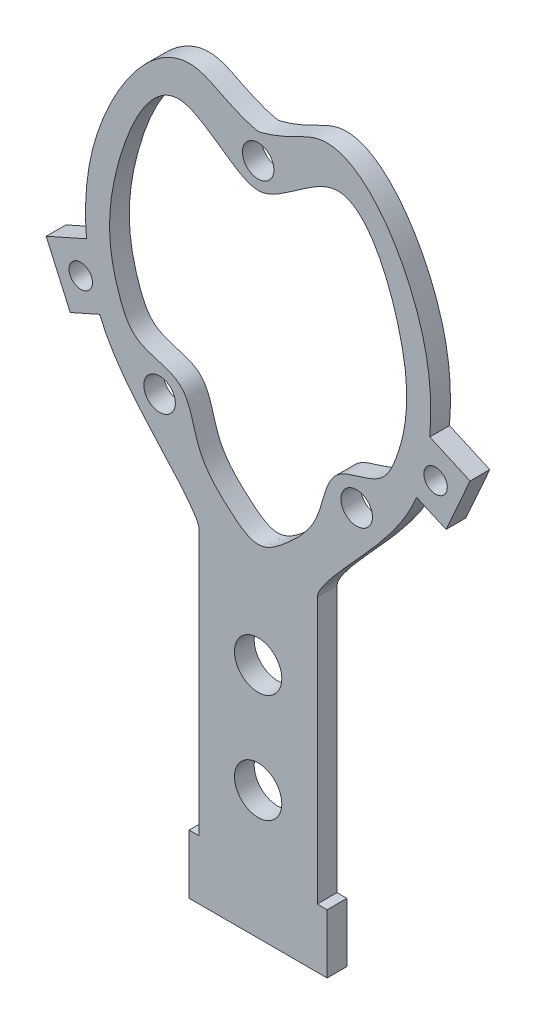
SolidWorks part; units mm, degrees
ref_plane "Front Plane" through (0, 0, 0) normal (0, 0, 1) x (1, 0, 0)
ref_plane "Top Plane" through (0, 0, 0) normal (0, 1, 0) x (1, 0, 0)
ref_plane "Right Plane" through (0, 0, 0) normal (1, 0, 0) x (0, 0, -1)
sketch "Sketch2" plane through (0, 0, 0) normal (0, 0, 1) x (1, 0, 0)
  line L0 (0, -0.0188) -> (0, -6.781) construction
  line L1 (-1.25, 4.75) -> (1.25, 4.75) construction
  line L2 (-4, 6.25) -> (4, 6.25) construction
  line L3 (-7.2, 1.5) -> (7.2, 1.5) construction
  line L4 (-6.25, -5.25) -> (6.25, -5.25) construction
  line L5 (-4, -6.25) -> (4, -6.25) construction
  line L6 (-3, -8.55) -> (3, -8.55) construction
  line L7 (-1.4, -10.55) -> (1.4, -10.55) construction
  line L8 (-5, -7.2) -> (-6.1491, -8.1642) construction
  line L9 (-7, -4) -> (7, -4) construction
  line L10 (0, 1.0146) -> (0, -5.7476) construction
  line L11 (-1, 7.15) -> (1, 7.15) construction
  line L12 (-3.1, 8.05) -> (3.1, 8.05) construction
  line L13 (-8.4144, 1.7962) -> (8.4144, 1.7962) construction
  line L14 (-6.1491, -8.1642) -> (6.1491, -8.1642) construction
  line L16 (-0.5007, -40.6671) -> (-6.3266, 25.9227) construction
  line L17 (-3, -12.1) -> (3, -12.1) construction
  line L18 (-8.6856, -2.4538) -> (8.6856, -2.4538) construction
  line L19 (6.2221, 24.7292) -> (0.3963, -41.8606) construction
  line L20 (-28.4032, 6.85) -> (28.4032, 6.85) construction
  line L21 (-7.2, 1.5) -> (-8.4144, 1.7962) construction
  line L22 (-8.6856, -2.4538) -> (-7.4495, -2.2683) construction
  line L23 (-3, -25.6) -> (-3.5, -25.6)
  line L24 (-3, -12.1) -> (3, -12.1) construction
  line L25 (-3, -12.1) -> (-3, -25.6)
  line L26 (-3, -25.6) -> (3, -25.6) construction
  line L27 (3, -12.1) -> (3, -25.6)
  line L28 (-3, -12.1) -> (3, -25.6) construction
  line L29 (-3, -25.6) -> (3, -12.1) construction
  line L30 (-3.5, -25.6) -> (3.5, -25.6) construction
  line L31 (-3.5, -25.6) -> (-3.5, -28.6)
  line L32 (-3.5, -28.6) -> (3.5, -28.6)
  line L33 (3.5, -25.6) -> (3.5, -28.6)
  line L34 (-3.5, -25.6) -> (3.5, -28.6) construction
  line L35 (-3.5, -28.6) -> (3.5, -25.6) construction
  line L36 (3.5, -25.6) -> (3, -25.6)
  circle A2 centre (0, -16.6) radius 1.2
  circle A3 centre (0, 5.55) radius 0.8
  circle A4 centre (-5, -7.2) radius 0.8
  circle A5 centre (5, -7.2) radius 0.8
  circle A6 centre (0, -22.1) radius 1.2
  spline S0 degree 3 poles (1.8069, 5.0163) (0, 4.0197) (-1.8069, 5.0163) (-4.9012, 7.7541) (-7.771, 1.1281) (-7.6313, -2.6614) (-6.2568, -5.758) (-3.5015, -5.7609) (-3.2301, -8.7844) (-1.7453, -10.314) (0, -11.6774) (1.7453, -10.314) (3.2301, -8.7844) (3.5015, -5.7609) (6.2568, -5.758) (7.6313, -2.6614) (7.771, 1.1281) (4.9012, 7.7541) (1.8069, 5.0163) (0, 4.0197) (-1.8069, 5.0163) knots -0.194127 -0.085189 -0.025607 0 0.025607 0.085189 0.194127 0.29881 0.326537 0.37337 0.421074 0.469791 0.5 0.530209 0.578926 0.62663 0.673463 0.70119 0.805873 0.914811 0.974393 1 1.025607 1.085189 1.194127 only from (0, 4.25) to (0, 4.25)
  spline S1 degree 3 poles (3, -12.1) (3.0581, -11.4359) (7.3722, -7.2617) (8.8163, -3.8196) (8.7952, 3.0882) (4.7299, 9.5027) (1.5431, 7.2852) (0.1384, 6.8487) (-0.1384, 6.8487) (-1.5431, 7.2852) (-4.7299, 9.5027) (-8.7952, 3.0882) (-8.8163, -3.8196) (-7.3722, -7.2617) (-3.0581, -11.4359) (-3, -12.1) knots 0.110532 0.110532 0.110532 0.110532 0.195871 0.310872 0.37508 0.502014 0.537662 0.553506 0.557026 0.57287 0.608518 0.735452 0.79966 0.914661 1 1 1 1
  point P5 (0, 0)
  point P9 (0, -6.25)
  point P40 (0, -2.2618)
  point P45 (0, -27.1)
  point P51 (0, 4.75)
  point P58 (0, 6.25)
  point P60 (0, 1.5)
  point P62 (0, -4)
  point P64 (0, -5.25)
  point P68 (0, -8.55)
  point P86 (0, -12.1)
  point P89 (0, 7.15)
  point P90 (0, 8.05)
  point P91 (0, 1.7962)
  point P92 (0, -2.4538)
  point P93 (0, -8.1642)
  point P100 (0, -10.55)
  point P101 (0, -25.6)
  point P102 (0, -18.85)
  dimension "D32" = 1
  dimension "D36" = 2
  dimension "D37" = 2
  dimension "D40" = 1.6
  dimension "D6" = 0.5
  dimension "D46" = 2.4
  dimension "D1" = 6
  dimension "D2" = 13.5
  dimension "D3" = 1.5
  dimension "D5" = 7.2
  dimension "D7" = 2.6
  dimension "D8" = 4.25
  dimension "D9" = 1.25
  dimension "D10" = 2
  dimension "D11" = 4
  dimension "D12" = 0.3
  dimension "D13" = 0.9
  dimension "D14" = 3.1
  dimension "D15" = 4
  dimension "D16" = 7
  dimension "D17" = 1.25
  dimension "D18" = 5.25
  dimension "D19" = 6.25
  dimension "D20" = 6.25
  dimension "D21" = 4
  dimension "D22" = 8.55
  dimension "D23" = 3
  dimension "D24" = 1.5
  dimension "D25" = 40
  dimension "D26" = 10
  dimension "D27" = 10.55
  dimension "D28" = 1.4
  dimension "D29" = 11.3
  dimension "D31" = 0.8
  dimension "D33" = 90
  dimension "D34" = 1
  dimension "D35" = 1.25
  dimension "D38" = 175
  dimension "D39" = 175
  dimension "D41" = 1.3
  dimension "D42" = 12.75
  dimension "D43" = 5
  dimension "D44" = 3
  dimension "D45" = 7
  dimension "D47" = 3.5
  dimension "D48" = 5.5
extrude "Boss-Extrude2" add sketch "Sketch2" along normal blind 1 separate body
sketch "Sketch3" plane through (0, 0, 0) normal (0, 0, 1) x (1, 0, 0)
  line L0 (-7.4013, -3.2882) -> (-10.1419, -4.5084) construction
  line L5 (-8.0114, -1.9179) -> (-6.7912, -4.6585)
  line L6 (-8.0114, -1.9179) -> (-10.752, -3.1381)
  line L8 (-10.752, -3.1381) -> (-9.5318, -5.8787)
  line L9 (-6.7912, -4.6585) -> (-9.5318, -5.8787)
  line L10 (0, 0) -> (0, -5.2835) construction
  line L11 (-8.0114, -1.9179) -> (-10.752, -3.1381)
  line L12 (-6.7912, -4.6585) -> (-9.5318, -5.8787)
  line L13 (7.4013, -3.2882) -> (10.1419, -4.5084) construction
  line L14 (6.7912, -4.6585) -> (9.5318, -5.8787)
  line L15 (8.0114, -1.9179) -> (10.752, -3.1381)
  line L16 (6.7912, -4.6585) -> (9.5318, -5.8787)
  line L17 (10.752, -3.1381) -> (9.5318, -5.8787)
  line L18 (8.0114, -1.9179) -> (10.752, -3.1381)
  line L19 (8.0114, -1.9179) -> (6.7912, -4.6585)
  point P5 (-9, -4)
  point P25 (9, -4)
  dimension "D1" = 3
  dimension "D2" = 24
  dimension "D3" = 1.25
  dimension "D4" = 9
  dimension "D5" = 4
extrude "Boss-Extrude3" add sketch "Sketch3" along normal blind 1 contours L9 L5 L6 L8 | L15 L19 L14 L17
sketch "Sketch4" plane through (0, 0, 0) normal (0, 0, 1) x (1, 0, 0)
  line L0 (-10.1419, -4.5084) -> (-9, -4) construction
  line L3 (-10.752, -3.1381) -> (-9.5318, -5.8787) construction
  line L6 (-8.7065, -2.2274) -> (-10.752, -3.1381) construction
  line L7 (0, 0) -> (0, -3.1391) construction
  circle A0 centre (-9, -4) radius 0.595
  circle A2 centre (9, -4) radius 0.595
  dimension "D1" = 1.19
  dimension "D2" = 1.25
extrude "Cut-Extrude10" cut sketch "Sketch4" along normal blind 10
